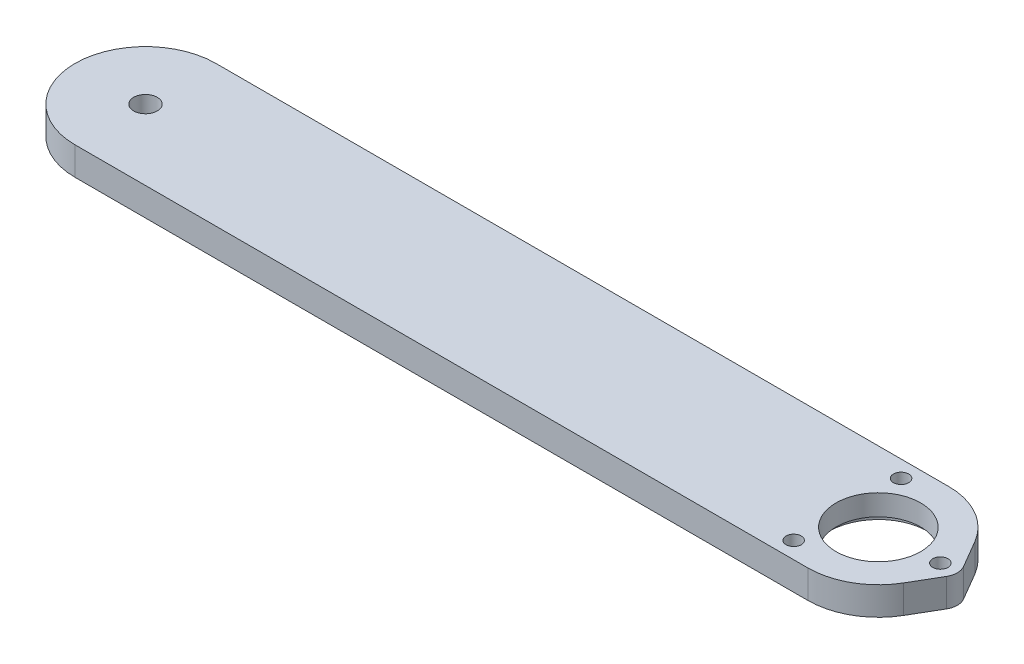
SolidWorks part; units mm, degrees
ref_plane "前视基准面" through (0, 0, 0) normal (0, 0, 1) x (1, 0, 0)
ref_plane "上视基准面" through (0, 0, 0) normal (0, 1, 0) x (1, 0, 0)
ref_plane "右视基准面" through (0, 0, 0) normal (1, 0, 0) x (0, 0, -1)
sketch "草图1" plane through (0, 0, 0) normal (0, 1, 0) x (1, 0, 0)
  line L0 (-65, 0) -> (65, 0) construction
  line L1 (-65, 12.5) -> (65, 12.5)
  line L2 (-65, -12.5) -> (65, -12.5)
  arc A0 (-65, 12.5) -> (-65, -12.5) centre (-65, 0) ccw
  arc A1 (65, -12.5) -> (65, 12.5) centre (65, 0) ccw
  point P2 (0, 0)
  dimension "D2" = 12.5
  dimension "D1" = 130
extrude "凸台-拉伸1" add sketch "草图1" along normal blind 5
sketch "草图10" plane through (0, 0, 0) normal (0, -1, 0) x (1, 0, 0)
  line L0 (75.7955, -6.3014) -> (78.5909, -1.5123)
  line L3 (75.7955, 6.3014) -> (78.5909, 1.5123)
  line L4 (75.7955, -6.3014) -> (75.7955, 6.3014)
  line L5 (76, 0) -> (77.5, 0) construction
  circle A5 centre (76, 0) radius 3 construction
  arc A6 (65, -12.5) -> (65, 12.5) centre (65, 0) ccw construction
  arc A7 (78.5909, -1.5123) -> (78.5909, 1.5123) centre (76, 0) ccw
  dimension "D1" = 6
  dimension "D2" = 1.5
extrude "凸台-拉伸5" add sketch "草图10" against normal up to surface (5 mm away) up to face at (0, 5, 0)
sketch "草图7" plane through (0, 5, 0) normal (0, 1, 0) x (1, 0, 0)
  circle A0 centre (65, 0) radius 7.5
  dimension "D1" = 15
extrude "切除-拉伸2" cut sketch "草图7" against normal up to next
sketch "草图8" plane through (0, 0, 0) normal (0, 1, 0) x (1, 0, 0)
  circle A0 centre (65, 0) radius 8.75
  dimension "D1" = 17.5
extrude "切除-拉伸3" cut sketch "草图8" along normal blind 1.3
sketch "草图9" plane through (0, 0, 0) normal (0, -1, 0) x (1, 0, 0)
  line L0 (65, 0) -> (54, 0) construction
  line L1 (65, 0) -> (59.5, 9.5263) construction
  circle A0 centre (65, 0) radius 11 construction
  circle A5 centre (59.5, 9.5263) radius 1.35
  circle A9 centre (76, 0) radius 1.35
  circle A10 centre (59.5, -9.5263) radius 1.35
  point P12 (65, 0)
  point P15 (65, 0)
  dimension "22" = 22
  dimension "D3" = 2.7
  dimension "D2" = 60
  dimension "D1" = 3
extrude "切除-拉伸4" cut sketch "草图9" against normal up to next
sketch "草图12" plane through (0, 5, 0) normal (0, 1, 0) x (1, 0, 0)
  circle A0 centre (-65, 0) radius 2.1
  dimension "D1" = 4.2
extrude "切除-拉伸5" cut sketch "草图12" against normal up to next
sketch "草图13" plane through (0, 0, 0) normal (0, -1, 0) x (1, 0, 0)
  circle A0 centre (59.5, 9.5263) radius 2.75
  circle A1 centre (76, 0) radius 2.75
  circle A2 centre (59.5, -9.5263) radius 2.75
  dimension "D1" = 5.5
